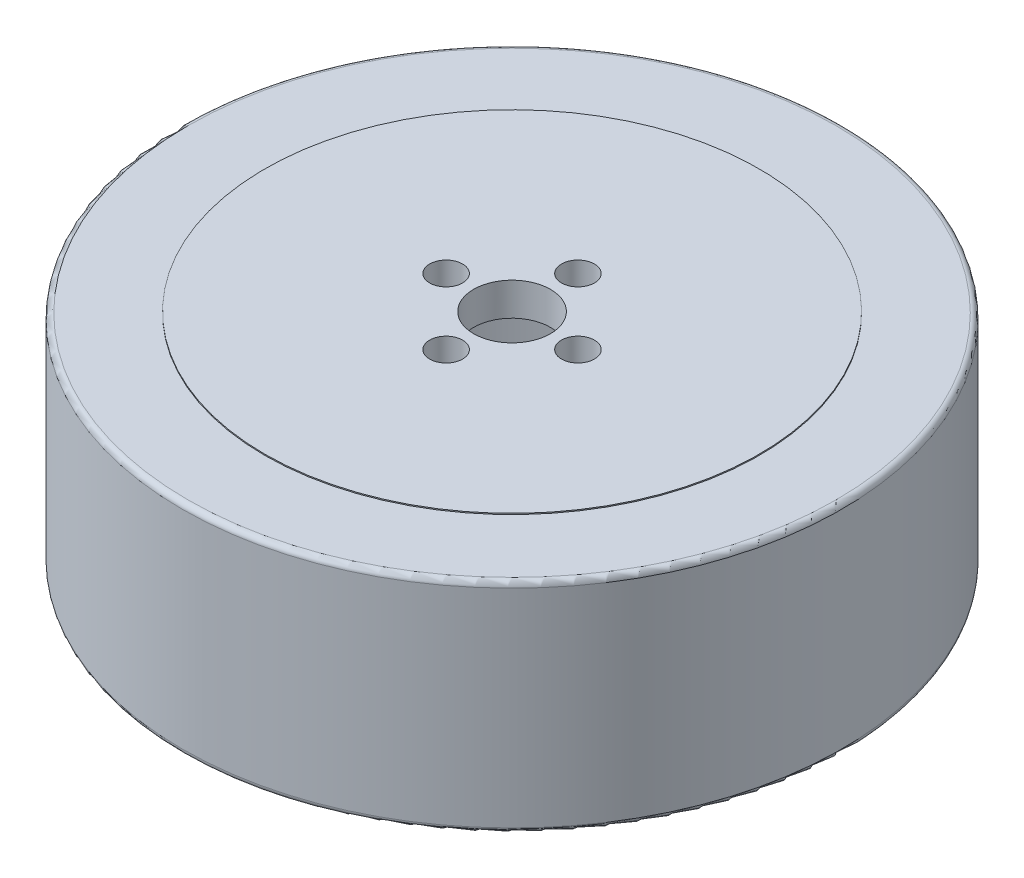
SolidWorks part; units mm, degrees
ref_plane "前视基准面" through (0, 0, 0) normal (0, 0, 1) x (1, 0, 0)
ref_plane "上视基准面" through (0, 0, 0) normal (0, 1, 0) x (1, 0, 0)
ref_plane "右视基准面" through (0, 0, 0) normal (1, 0, 0) x (0, 0, -1)
other "Configuration Table"
sketch "草图1" plane through (0, 0, 0) normal (0, 1, 0) x (1, 0, 0)
  line L0 (-10.134, 0) -> (10.3365, 0) construction
  line L1 (0, 10.1135) -> (0, -8.3696) construction
  circle A0 centre (0, 0) radius 30
  circle A2 centre (0, 6) radius 1.5
  circle A3 centre (0, 0) radius 3.5
  circle A4 centre (6, 0) radius 1.5
  circle A5 centre (0, -6) radius 1.5
  circle A6 centre (-6, 0) radius 1.5
  point P19 (0, 0)
  dimension "D1" = 60
  dimension "D2" = 7
  dimension "D3" = 3
  dimension "D4" = 6
  dimension "D5" = 4
extrude "凸台-拉伸1" add sketch "草图1" along normal blind 20
sketch "草图2" plane through (0, 0, 0) normal (0, -1, 0) x (-1, 0, 0)
  circle A0 centre (0, 0) radius 21
  dimension "D1" = 42
extrude "切除-拉伸1" cut sketch "草图2" against normal blind 17
sketch "草图3" plane through (0, 20, 0) normal (0, 1, 0) x (1, 0, 0)
  circle A0 centre (0, 0) radius 22.5
  circle A1 centre (0, 0) radius 30
  dimension "D1" = 45
extrude "切除-拉伸2" cut sketch "草图3" against normal blind 0.1
fillet "圆角1" radius 0.5 2 edges at (0, 19.9, 30) (0, 0, 30)
